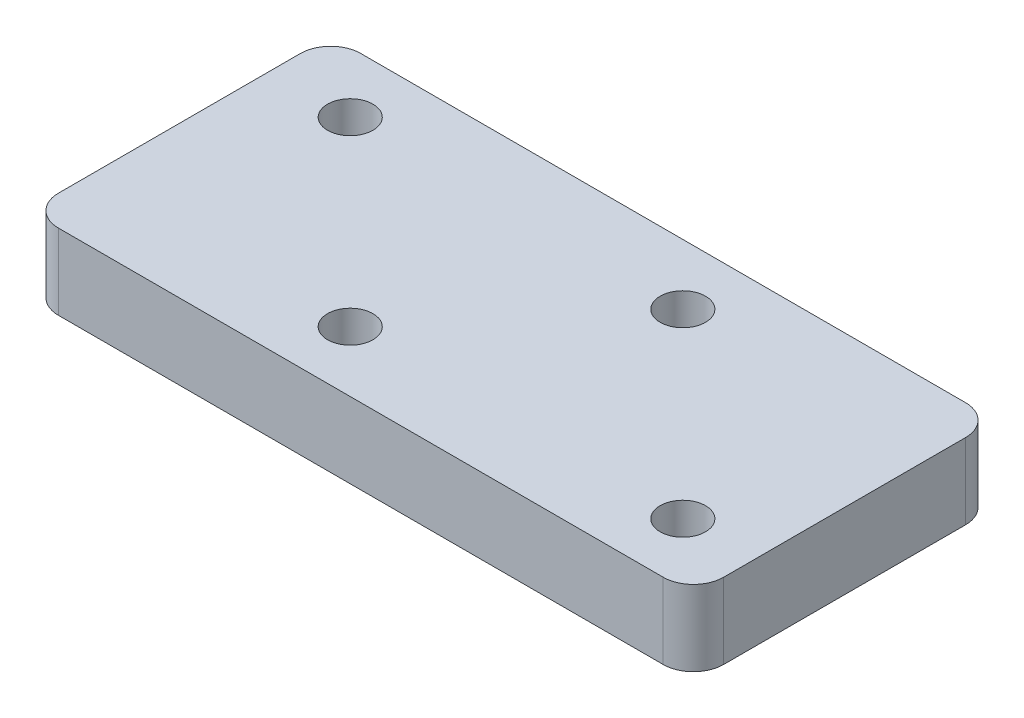
SolidWorks part; units mm, degrees
ref_plane "前视基准面" through (0, 0, 0) normal (0, 0, 1) x (1, 0, 0)
ref_plane "上视基准面" through (0, 0, 0) normal (0, 1, 0) x (1, 0, 0)
ref_plane "右视基准面" through (0, 0, 0) normal (1, 0, 0) x (0, 0, -1)
sketch "草图1" plane through (0, 0, 0) normal (0, 1, 0) x (1, 0, 0)
  line L0 (5.3, 16) -> (27.3, 16) construction
  line L1 (0, 0) -> (44, 0)
  line L2 (0, 0) -> (0, 20)
  line L3 (0, 20) -> (44, 20)
  line L4 (44, 0) -> (44, 20)
  circle A0 centre (5.3, 16) radius 1.5
  circle A1 centre (17.3, 4) radius 1.5
  circle A2 centre (27.3, 16) radius 1.5
  circle A3 centre (39.3, 4) radius 1.5
  dimension "D1" = 3
  dimension "D2" = 5.3
  dimension "D4" = 12
  dimension "D5" = 4
  dimension "D6" = 12
  dimension "D3" = 20
  dimension "D7" = 44
  dimension "D9" = 22
  dimension "D8" = 2
extrude "凸台-拉伸1" add sketch "草图1" along normal blind 5
fillet "圆角1" radius 2 4 edges at (44, 2.5, -20) (44, 2.5, 0) (0, 2.5, 0) (0, 2.5, -20)
